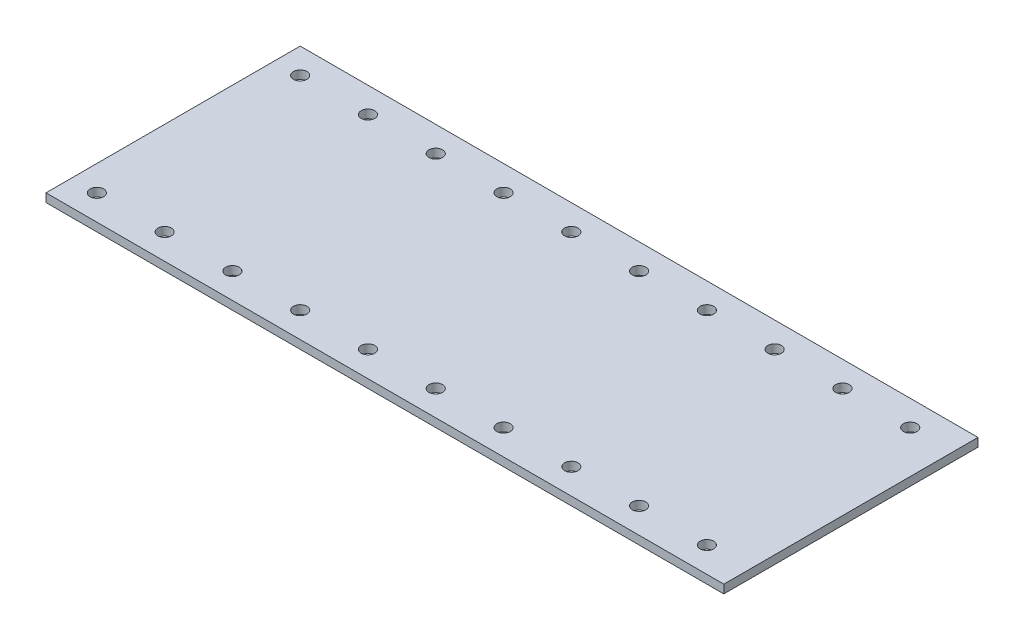
SolidWorks part; units mm, degrees
other "Connection Feature" parameters "D1"=64.3461, "D2"=158.0247
ref_plane "Front Plane" through (0, 0, 0) normal (0, 0, 1) x (1, 0, 0)
ref_plane "Top Plane" through (0, 0, 0) normal (0, 1, 0) x (1, 0, 0)
ref_plane "Right Plane" through (0, 0, 0) normal (1, 0, 0) x (0, 0, -1)
sketch "Sketch1" plane through (0, 0, 0) normal (0, 1, 0) x (1, 0, 0)
  line L1 (-100, 37.5) -> (100, 37.5)
  line L2 (-100, 37.5) -> (-100, -37.5)
  line L3 (-100, -37.5) -> (100, -37.5)
  line L4 (100, 37.5) -> (100, -37.5)
  line L5 (-100, 37.5) -> (100, -37.5) construction
  line L6 (-100, -37.5) -> (100, 37.5) construction
  point P0 (0, 0)
extrude "Boss-Extrude1" add sketch "Sketch1" along normal blind 2.5
hole_wizard "Ø4.0mm Dowel Hole1" positions "Sketch3" profile "Sketch4" hole size "Ø4.0" standard "ANSI Metric" end condition through all
sketch "Sketch3" plane through (0, 2.5, 0) normal (0, 1, 0) x (1, 0, 0)
  line L0 (100, 37.5) -> (-100, 37.5) construction
  line L1 (-100, 37.5) -> (-100, -37.5) construction
  line L2 (0, 0) -> (-100, 0) construction
  line L4 (-92.5, 30) -> (-92.5, -30) construction
  point P0 (-92.5, 30)
  point P2 (-92.5, -30)
  point P17 (-92.5, 0)
  dimension "D1" = 7.5
  dimension "D2" = 7.5
sketch "Sketch4" plane through (-92.5, 2.5, -30) normal (1, 0, 0) x (0, 0, 1)
  line L0 (0, 0) -> (0, 2.5)
  line L1 (0, 2.5) -> (2.025, 2.5)
  line L2 (2, 2.475) -> (2, 0)
  line L5 (2, 0) -> (0, 0)
  line L7 (2.025, 2.5) -> (2, 2.475)
  line L8 (-2.025, 2.5) -> (-2, 2.475) construction
  line L11 (0, -6.35) -> (0, 107.95) construction
  dimension "Thru Hole Dia." = 4
  dimension "Thru Hole Depth" = 2.5
  dimension "Far C'Sink Dia." = 4.05
  dimension "Far C'Sink Angle" = 90
pattern_linear "LPattern1" count 10 spacing 20 along (1, 0, 0) of "Ø4.0mm Dowel Hole1"
other "Configuration Table"
